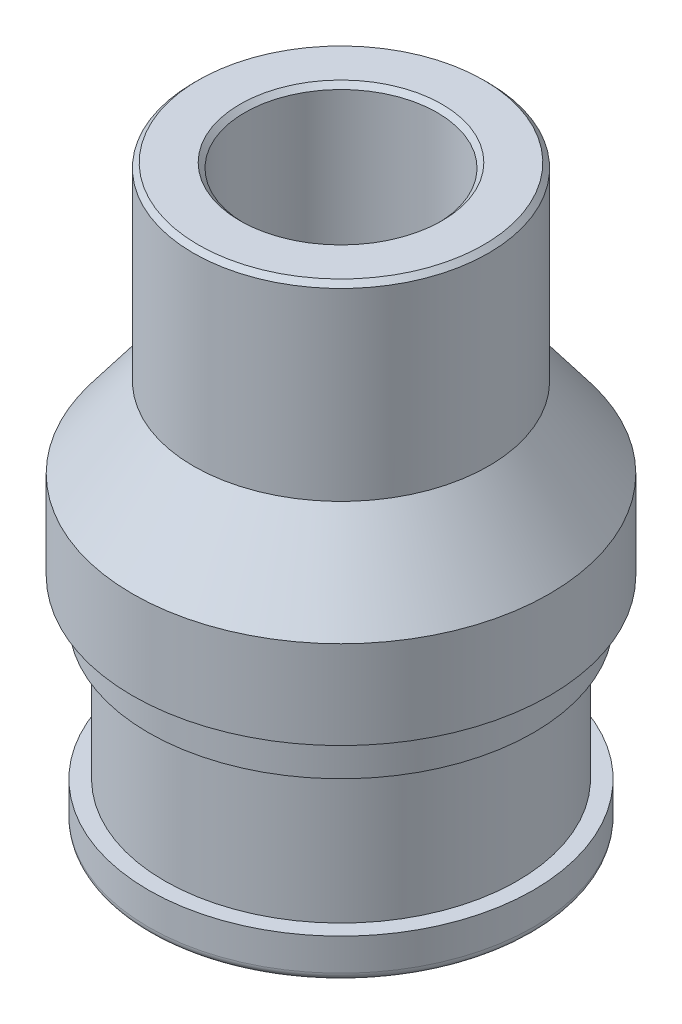
SolidWorks part; units mm, degrees
material "Custom Stainless Steel 1"
ref_plane "Front Plane" through (0, 0, 0) normal (0, 0, 1) x (1, 0, 0)
ref_plane "Top Plane" through (0, 0, 0) normal (0, 1, 0) x (1, 0, 0)
ref_plane "Right Plane" through (0, 0, 0) normal (1, 0, 0) x (0, 0, -1)
sketch "Sketch1" plane through (0, 1, 0) normal (0, -1, 0) x (-1, 0, 0)
  circle A0 centre (-12.3501, 22.3386) radius 4.6
  circle A1 centre (-12.3501, 22.3386) radius 3
  dimension "D1" = 9.2
  dimension "D2" = 6
extrude "Boss-Extrude1" add sketch "Sketch1" along normal blind 5.9
chamfer "Chamfer1" distance 0.15 angle 45 1 edges at (12.3501, 1, -26.9386)
chamfer "Chamfer2" distance 0.15 angle 45 1 edges at (12.3501, 1, -25.3386)
sketch "Sketch2" plane through (0, -4.9, 0) normal (0, -1, 0) x (-1, 0, 0)
  circle A0 centre (-12.3501, 22.3386) radius 4.6
  circle A1 centre (-12.3501, 22.3386) radius 4.6 construction
extrude "Boss-Extrude2" add sketch "Sketch2" along normal blind 2.5 draft 37.235 draft outward yes
sketch "Sketch3" plane through (0, -4.9, 0) normal (0, 1, 0) x (1, 0, 0)
  circle A0 centre (12.3501, 22.3386) radius 3
  circle A3 centre (12.3501, 22.3386) radius 3 construction
extrude "Cut-Extrude1" cut sketch "Sketch3" against normal up to surface (2.5 mm away) up to face at (12.3501, -7.4, -28.8386)
sketch "Sketch4" plane through (0, -7.4, 0) normal (0, -1, 0) x (-1, 0, 0)
  circle A0 centre (-12.3501, 22.3386) radius 6.5
  circle A1 centre (-12.3501, 22.3386) radius 6.5 construction
  circle A2 centre (-12.3501, 22.3386) radius 3
  circle A3 centre (-12.3501, 22.3386) radius 3 construction
extrude "Boss-Extrude3" add sketch "Sketch4" along normal blind 4
sketch "Sketch5" plane through (0, -11.4, 0) normal (0, -1, 0) x (1, 0, 0)
  circle A0 centre (12.3501, -22.3386) radius 5.5
  circle A2 centre (12.3501, -22.3386) radius 3
  circle A3 centre (12.3501, -22.3386) radius 3 construction
  dimension "D1" = 11
extrude "Boss-Extrude4" add sketch "Sketch5" along normal blind 5.5
sketch "Sketch6" plane through (0, -11.4, 0) normal (0, -1, 0) x (1, 0, 0)
  line L1 (18.8501, -22.3386) -> (17.8501, -22.3386) construction
  circle A0 centre (12.3501, -22.3386) radius 6.5
  circle A1 centre (12.3501, -22.3386) radius 6.5 construction
  circle A2 centre (12.3501, -22.3386) radius 6
  circle A3 centre (12.3501, -22.3386) radius 5.5 construction
  point P10 (18.3501, -22.3386)
extrude "Cut-Extrude2" cut sketch "Sketch6" against normal blind 1.25
sketch "Sketch7" plane through (0, -16.9, 0) normal (0, -1, 0) x (-1, 0, 0)
  circle A0 centre (-12.3501, 22.3386) radius 5.5
  circle A1 centre (-12.3501, 22.3386) radius 5.5 construction
  circle A2 centre (-12.3501, 22.3386) radius 6
  circle A3 centre (-12.3501, 22.3386) radius 6 construction
extrude "Boss-Extrude5" add sketch "Sketch7" against normal blind 1.25
fillet "Fillet1" radius 0.25 1 edges at (12.3501, -16.9, -28.3386)
sketch "Sketch8" plane through (0, -16.9, 0) normal (0, -1, 0) x (-1, 0, 0)
  circle A0 centre (-12.3501, 22.3386) radius 4.5
  dimension "D1" = 9
extrude "Cut-Extrude3" cut sketch "Sketch8" against normal blind 4
chamfer "Chamfer4" distance 0.15 angle 45 1 edges at (12.3501, -16.9, -26.8386)
chamfer "Chamfer5" distance 0.15 angle 45 1 edges at (12.3501, -12.9, -25.3386)
